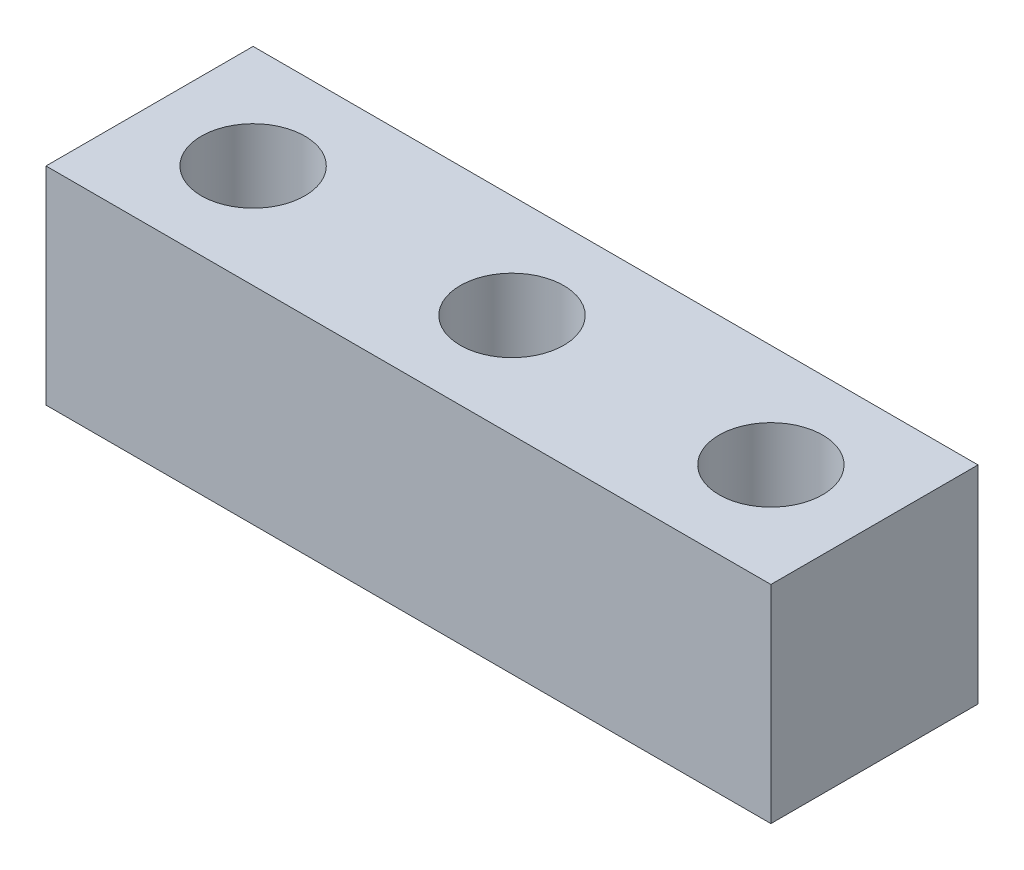
SolidWorks part; units mm, degrees
material "Acrylic (Medium-high impact)"
ref_plane "Front Plane" through (0, 0, 0) normal (0, 0, 1) x (1, 0, 0)
ref_plane "Top Plane" through (0, 0, 0) normal (0, 1, 0) x (1, 0, 0)
ref_plane "Right Plane" through (0, 0, 0) normal (1, 0, 0) x (0, 0, -1)
sketch "Sketch1" plane through (0, 0, 0) normal (0, 1, 0) x (1, 0, 0)
  line L0 (-15.875, 0) -> (15.875, 0) construction
  line L1 (22.225, 6.35) -> (-22.225, 6.35)
  line L2 (22.225, 6.35) -> (22.225, -6.35)
  line L3 (22.225, -6.35) -> (-22.225, -6.35)
  line L4 (-22.225, 6.35) -> (-22.225, -6.35)
  line L5 (22.225, 6.35) -> (-22.225, -6.35) construction
  line L6 (22.225, -6.35) -> (-22.225, 6.35) construction
  circle A0 centre (-15.875, 0) radius 3.175
  circle A1 centre (15.875, 0) radius 3.175
  circle A2 centre (0, 0) radius 3.175
  point P0 (0, 0)
  point P10 (0, 0)
  dimension "D4" = 6.35
  dimension "D1" = 44.45
  dimension "D2" = 12.7
  dimension "D3" = 31.75
extrude "Boss-Extrude1" add sketch "Sketch1" along normal blind 12.7
sketch "Sketch2" plane through (0, 0, 6.35) normal (0, 0, 1) x (1, 0, 0)
  circle A0 centre (7.62, 6.35) radius 2.3813
  circle A1 centre (-7.62, 6.35) radius 2.3813
  dimension "D1" = 4.7625
  dimension "D2" = 6.35
  dimension "D3" = 7.62
  dimension "D4" = 15.24
extrude "Cut-Extrude1" [suppressed] cut sketch "Sketch2" against normal through all
